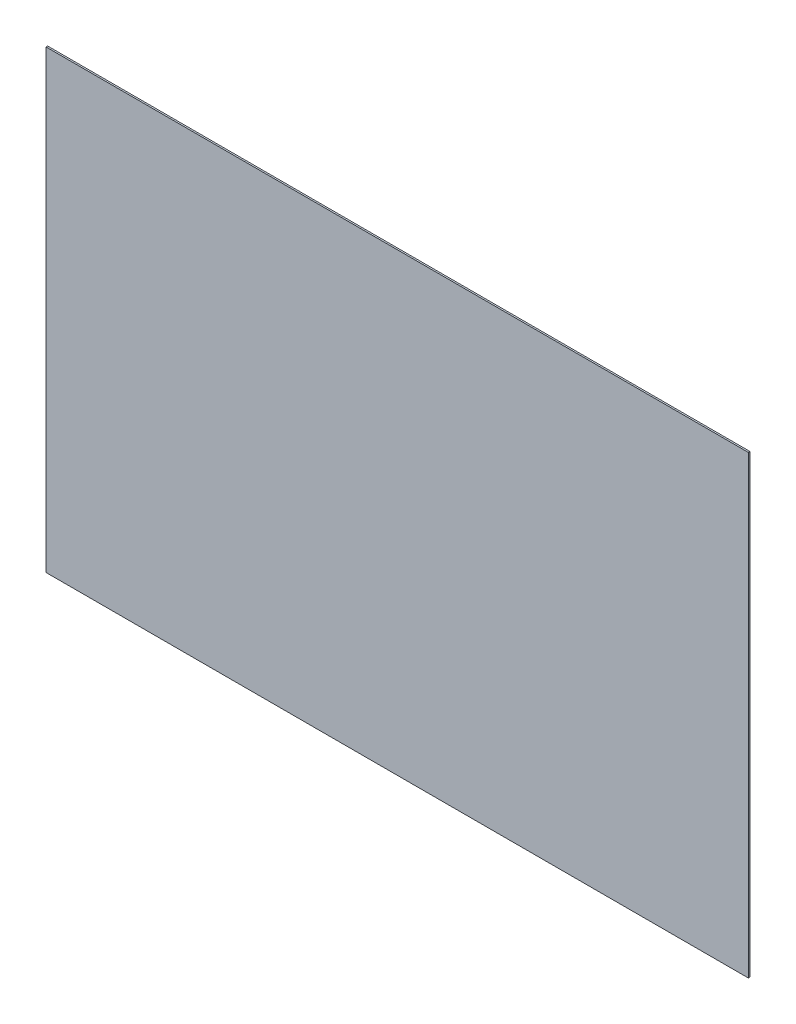
SolidWorks part; units mm, degrees
material "Acrylic (Medium-high impact)"
ref_plane "Front Plane" through (0, 0, 0) normal (0, 0, 1) x (1, 0, 0)
ref_plane "Top Plane" through (0, 0, 0) normal (0, 1, 0) x (1, 0, 0)
ref_plane "Right Plane" through (0, 0, 0) normal (1, 0, 0) x (0, 0, -1)
sketch "Sketch1" plane through (0, 0, 0) normal (0, 0, 1) x (1, 0, 0)
  line L1 (0, 0) -> (-685.8, 0)
  line L2 (0, 0) -> (0, 444.5)
  line L3 (0, 444.5) -> (-685.8, 444.5)
  line L4 (-685.8, 0) -> (-685.8, 444.5)
  dimension "D1" = 685.8
  dimension "D2" = 444.5
extrude "Boss-Extrude1" add sketch "Sketch1" along normal blind 1.5875
